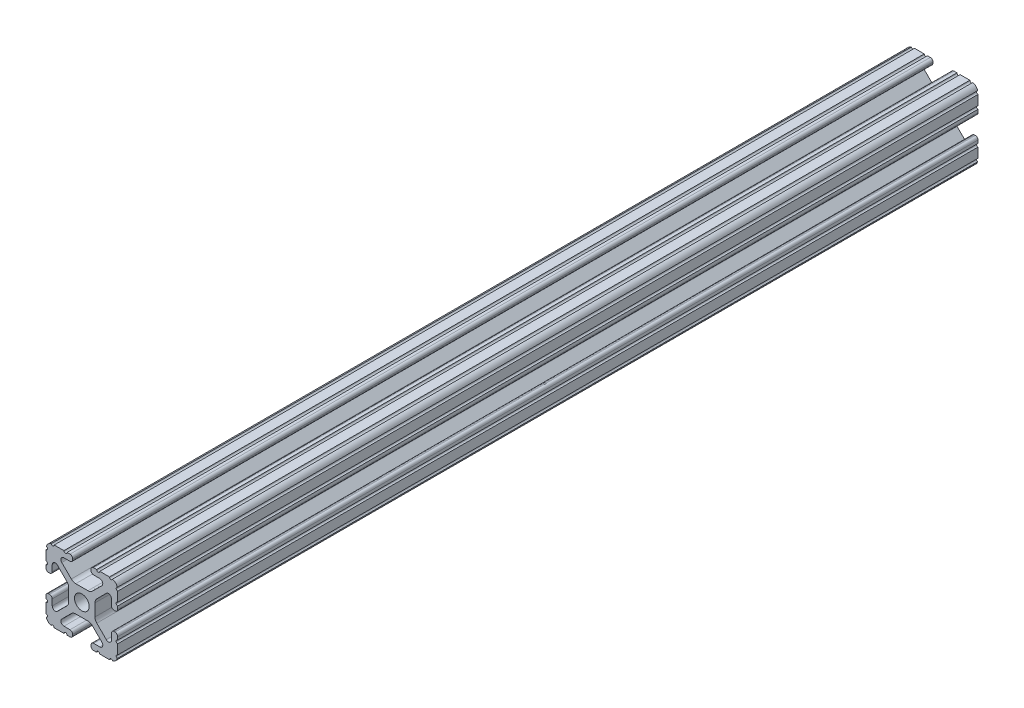
SolidWorks part; units mm, degrees
ref_plane "Front Plane" through (0, 0, 0) normal (0, 0, 1) x (1, 0, 0)
ref_plane "Top Plane" through (0, 0, 0) normal (0, 1, 0) x (1, 0, 0)
ref_plane "Right Plane" through (0, 0, 0) normal (1, 0, 0) x (0, 0, -1)
sketch "Sketch2" plane through (0, 0, 0) normal (0, 0, 1) x (1, 0, 0)
  line L0 (0, 12.7) -> (0, -12.7) construction
  line L1 (-12.7, 0) -> (12.7, 0) construction
  line L2 (3.2512, -12.7) -> (12.7, -12.7)
  line L3 (12.7, -12.7) -> (12.7, -3.2512)
  line L4 (3.2512, -12.7) -> (3.2512, -10.4902)
  line L5 (3.2512, -10.4902) -> (8.9276, -10.4902)
  line L6 (8.9276, -10.4902) -> (3.0856, -4.6482)
  line L7 (0, 0) -> (12.7, -12.7) construction
  line L8 (12.7, -3.2512) -> (10.4902, -3.2512)
  line L9 (10.4902, -3.2512) -> (10.4902, -8.9276)
  line L10 (10.4902, -8.9276) -> (4.6482, -3.0856)
  circle A0 centre (0, 0) radius 2.6035
  arc A1 (6.3485, -10.4902) -> (7.1039, -8.6665) centre (6.3485, -9.4219) ccw construction
  point P8 (0, -4.6482)
  dimension "Center Hole Diameter" = 5.207
  dimension "Rail Height" = 25.4
  dimension "Rail Width" = 25.4
  dimension "T-Slot Width" = 6.5024
  dimension "Slot Inner Width" = 14.8336
  dimension "Thickness" = 2.2098
  dimension "Slot Depth" = 5.842
  dimension "D1" = 2.2098
sketch "Sketch3" plane through (0, 0, 0) normal (1, 0, 0) x (0, 0, -1)
  line L0 (-152.4, -12.7) -> (152.4, -12.7) construction
  line L1 (-127, 0) -> (127, 0) construction
  dimension "Length" = 304.8
sketch "Sketch4" plane through (0, 0, 0) normal (0, 0, 1) x (1, 0, 0)
  line L0 (4.1904, -12.7) -> (10.1173, -12.7)
  line L1 (3.2512, -12.7) -> (12.7, -12.7) construction
  line L2 (3.2512, -12.7) -> (3.2512, -10.4902) construction
  line L3 (3.2512, -10.4902) -> (8.9276, -10.4902) construction
  line L4 (3.2512, -11.4294) -> (3.2512, -11.7608)
  line L5 (4.1904, -10.4902) -> (6.3485, -10.4902)
  line L6 (0, -4.6482) -> (2.164, -4.6482)
  line L7 (8.9276, -10.4902) -> (3.0856, -4.6482) construction
  line L8 (3.7373, -5.2999) -> (7.1039, -8.6665)
  line L9 (12.7, -12.7) -> (12.7, -3.2512) construction
  line L10 (10.4902, -8.9276) -> (4.6482, -3.0856) construction
  line L11 (10.4902, -3.2512) -> (10.4902, -8.9276) construction
  line L12 (10.4902, -6.3485) -> (10.4902, -4.1904)
  line L13 (12.7, -3.2512) -> (10.4902, -3.2512) construction
  line L14 (11.4294, -3.2512) -> (11.7608, -3.2512)
  line L15 (12.7, -4.1904) -> (12.7, -10.1173)
  line L16 (8.6665, -7.1039) -> (5.2999, -3.7373)
  line L17 (4.6482, 0) -> (4.6482, -2.164)
  line L18 (-12.7, 0) -> (12.7, 0) construction
  line L19 (0, -4.6482) -> (0, -2.6035)
  line L20 (0, 12.7) -> (0, -12.7) construction
  line L21 (4.6482, 0) -> (2.6035, 0)
  arc A0 (3.2512, -11.7608) -> (4.1904, -12.7) centre (4.1904, -11.7608) ccw
  arc A2 (3.2512, -11.4294) -> (4.1904, -10.4902) centre (4.1904, -11.4294) cw
  arc A3 (6.3485, -10.4902) -> (7.1039, -8.6665) centre (6.3485, -9.4219) ccw
  arc A4 (2.164, -4.6482) -> (3.7373, -5.2999) centre (2.164, -6.8732) cw
  arc A5 (10.1173, -12.7) -> (12.7, -10.1173) centre (10.1173, -10.1173) ccw
  arc A6 (8.6665, -7.1039) -> (10.4902, -6.3485) centre (9.4219, -6.3485) ccw
  arc A7 (10.4902, -4.1904) -> (11.4294, -3.2512) centre (11.4294, -4.1904) cw
  arc A8 (11.7608, -3.2512) -> (12.7, -4.1904) centre (11.7608, -4.1904) cw
  arc A9 (5.2999, -3.7373) -> (4.6482, -2.164) centre (6.8732, -2.164) cw
  circle A10 centre (0, 0) radius 2.6035 construction
  arc A11 (0, -2.6035) -> (2.6035, 0) centre (0, 0) ccw
  dimension "D1" = 2.5827
  dimension "D2" = 2.225
  dimension "D3" = 0.9392
extrude "Boss-Extrude1" add sketch "Sketch4" along normal mid plane 304.8
sketch "Sketch5" plane through (0, 0, 0) normal (0, 0, 1) x (1, 0, 0)
  line L0 (3.2512, -12.7) -> (12.7, -12.7) construction
  line L1 (4.1904, -10.4902) -> (6.3485, -10.4902) construction
  line L3 (0, 0) -> (12.7, -12.7) construction
  line L4 (6.3485, -10.4902) -> (6.3485, -12.7) construction
  line L5 (8.9276, -10.4902) -> (3.0856, -4.6482) construction
  circle A0 centre (10.3562, -12.7) radius 0.5524
  circle A1 centre (5.796, -12.7) radius 0.5524
  circle A2 centre (12.7, -10.3562) radius 0.5524
  circle A3 centre (12.7, -5.796) radius 0.5524
  point P10 (5.2694, -10.4902)
  point P12 (9.4219, -6.3485)
  dimension "D1" = 1.1049
extrude "Cut-Extrude1" cut sketch "Sketch5" against normal through all both and the other way through all
mirror "Mirror1" about plane through (0, 0, 0) normal (1, 0, 0) of bodies 137 134
mirror "Mirror2" about plane through (0, 0, 0) normal (0, 1, 0) of bodies 135
sketch "Sketch6" plane through (12.7, 0, 0) normal (1, 0, 0) x (0, 0, -1)
  line L0 (-152.4, 0) -> (152.4, 0)
  line L1 (-152.4, -2.164) -> (-152.4, 2.164) construction
  line L2 (152.4, -2.164) -> (152.4, 2.164) construction
  circle A0 centre (0, 0) radius 3.2639
  dimension "D1" = 6.5278
extrude "Cut-Extrude2" cut sketch "Sketch6" against normal through all contours A0
equation "\"D1@Boss-Extrude1\"=\"Length@Sketch3\""
equation "\"D1@Sketch2\"=\"Thickness@Sketch2\""
equation "\"D2@Sketch4\"=\"Slot Inner Width@Sketch2\"*0.15"
equation "\"D1@Sketch4\"=\"D3@Sketch4\"*2.75"
equation "\"D3@Sketch4\"=\"Thickness@Sketch2\"*0.425"
equation "\"D1@Sketch5\"=\"Thickness@Sketch2\"*0.5"
